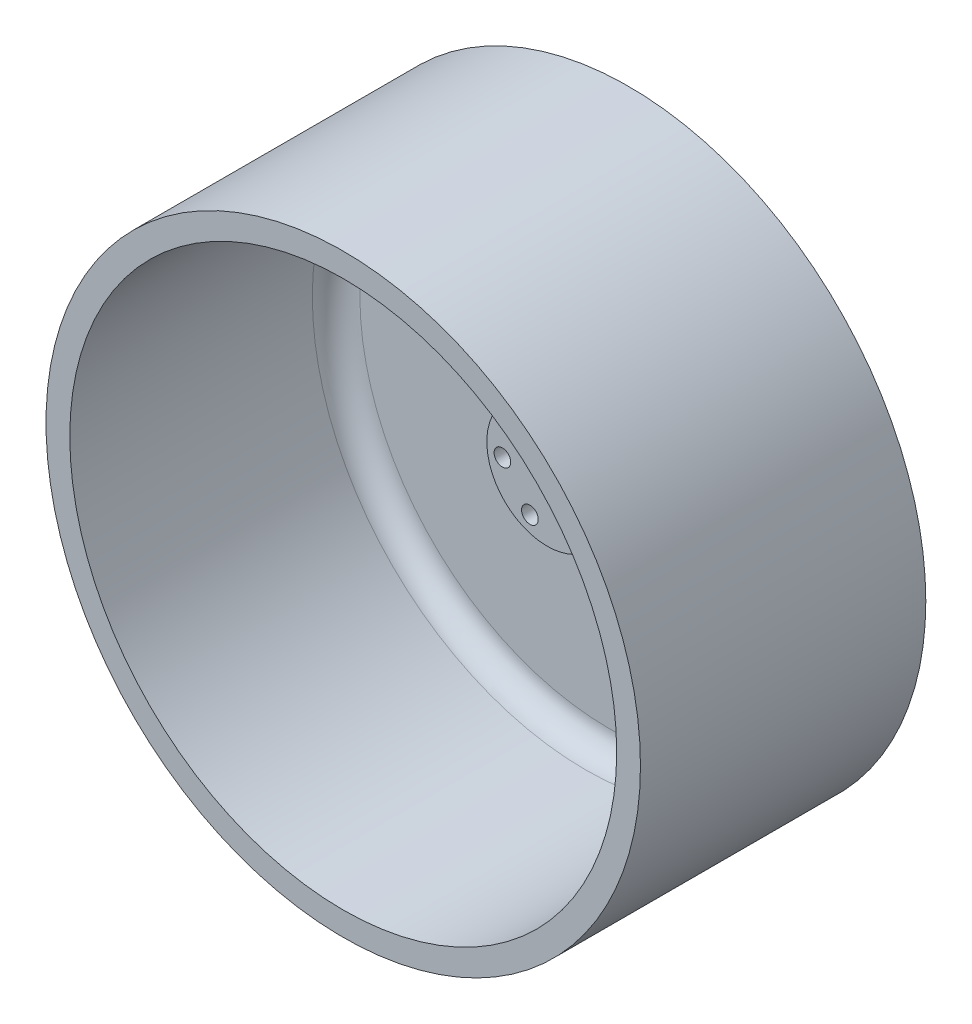
SolidWorks part; units mm, degrees
ref_plane "Front Plane" through (0, 0, 0) normal (0, 0, 1) x (1, 0, 0)
ref_plane "Top Plane" through (0, 0, 0) normal (0, 1, 0) x (1, 0, 0)
ref_plane "Right Plane" through (0, 0, 0) normal (1, 0, 0) x (0, 0, -1)
sketch "Sketch1" plane through (0, 0, 0) normal (0, 0, 1) x (1, 0, 0)
  circle A0 centre (0, 0) radius 62.5
  dimension "D1" = 125
extrude "Boss-Extrude1" add sketch "Sketch1" along normal blind 60
sketch "Sketch2" plane through (0, 0, 60) normal (0, 0, 1) x (1, 0, 0)
  circle A0 centre (0, 0) radius 57.5
  circle A1 centre (0, 0) radius 62.5 construction
  dimension "D1" = 5
extrude "Cut-Extrude1" cut sketch "Sketch2" against normal offset from surface (56 mm away) 4 up to face at (62.5, 0, 0)
ref_plane "Plane1" through (0, 0, 30) normal (0, 0, 1) x (1, 0, 0)
sketch "Sketch3" plane through (0, 0, 4) normal (0, 0, 1) x (1, 0, 0)
  circle A0 centre (0, 0) radius 12.7
  dimension "D1" = 25.4
extrude "Boss-Extrude2" add sketch "Sketch3" along normal offset from surface (13.11 mm away) 12.89 up to plane "Plane1"
sketch "Sketch4" plane through (0, 0, 17.11) normal (0, 0, 1) x (1, 0, 0)
  line L1 (5.7843, -7.536) -> (9.4186, 1.2413) construction
  line L2 (9.4186, 1.2413) -> (3.6342, 8.7774) construction
  line L3 (3.6342, 8.7774) -> (-5.7843, 7.536) construction
  line L4 (-5.7843, 7.536) -> (-9.4186, -1.2413) construction
  line L5 (-9.4186, -1.2413) -> (-3.6342, -8.7774) construction
  line L6 (-3.6342, -8.7774) -> (5.7843, -7.536) construction
  circle A0 centre (0, 0) radius 9.5 construction
  circle A1 centre (-5.7843, 7.536) radius 1.75
  circle A2 centre (-9.4186, -1.2413) radius 1.75
  circle A3 centre (-3.6342, -8.7774) radius 1.75
  circle A4 centre (5.7843, -7.536) radius 1.75
  circle A5 centre (9.4186, 1.2413) radius 1.75
  circle A6 centre (3.6342, 8.7774) radius 1.75
  circle A7 centre (0, 0) radius 3
  dimension "D1" = 19
  dimension "D2" = 3.5
  dimension "D3" = 6
extrude "Cut-Extrude2" cut sketch "Sketch4" against normal through all
sketch "Sketch5" plane through (0, 0, 0) normal (0, 0, -1) x (-1, 0, 0)
  circle A0 centre (-9.4186, 1.2413) radius 3.25
  circle A1 centre (-3.6342, 8.7774) radius 3.25
  circle A2 centre (5.7843, 7.536) radius 3.25
  circle A3 centre (9.4186, -1.2413) radius 3.25
  circle A4 centre (3.6342, -8.7774) radius 3.25
  circle A5 centre (-5.7843, -7.536) radius 3.25
  dimension "D1" = 6.5
extrude "Cut-Extrude3" cut sketch "Sketch5" against normal blind 3
fillet "Fillet1" radius 5 1 edges at (57.5, 0, 4)
fillet "Fillet2" radius 10 1 edges at (12.7, 0, 4)
